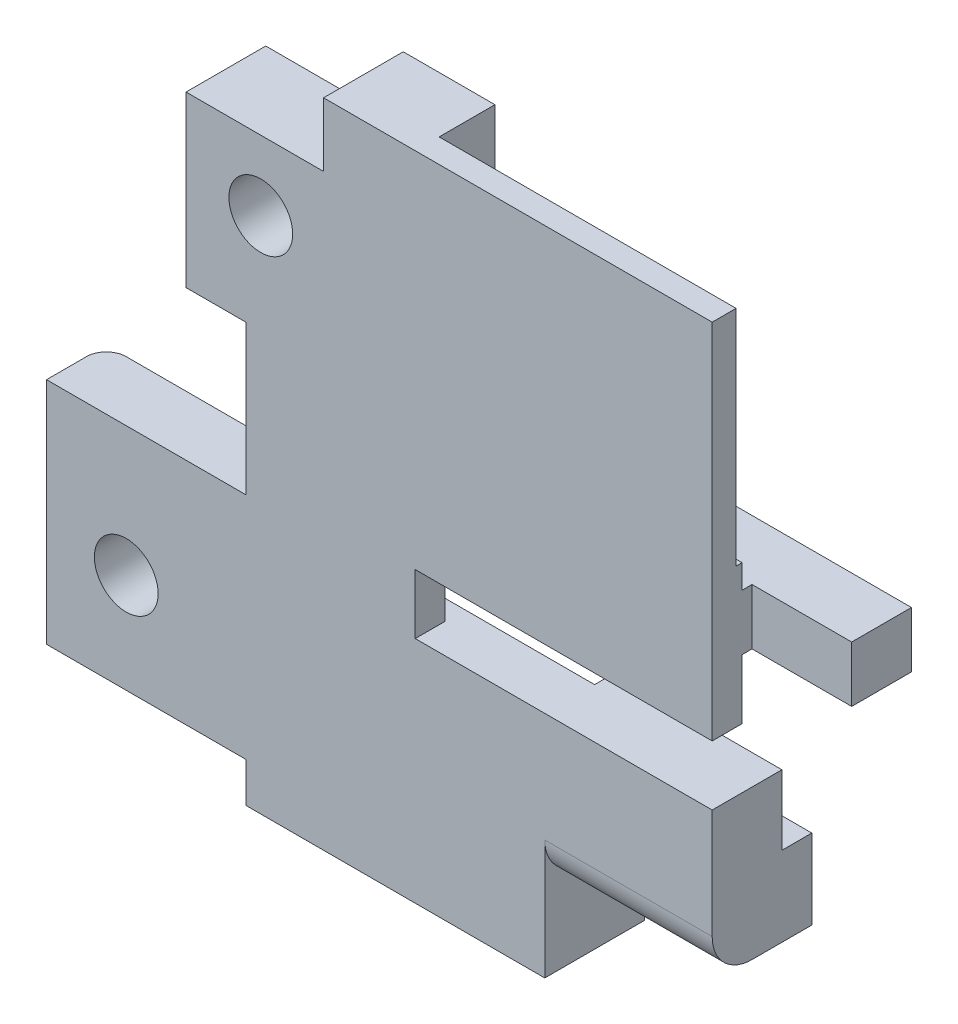
SolidWorks part; units mm, degrees
ref_plane "前视基准面" through (0, 0, 0) normal (0, 0, 1) x (1, 0, 0)
ref_plane "上视基准面" through (0, 0, 0) normal (0, 1, 0) x (1, 0, 0)
ref_plane "右视基准面" through (0, 0, 0) normal (1, 0, 0) x (0, 0, -1)
other "Configuration Table"
sketch "草图1" plane through (0, 0, 0) normal (0, 0, 1) x (1, 0, 0)
  line L1 (-4, 6.5) -> (6, 6.5)
  line L2 (-4, 6.5) -> (-4, -5)
  line L3 (-4, -5) -> (6, -5)
  line L4 (6, 6.5) -> (6, -5)
  circle A0 centre (0, 0) radius 1.6
  dimension "D1" = 3.2
  dimension "D2" = 5
  dimension "D3" = 4
  dimension "D4" = 11.5
  dimension "D5" = 10
extrude "凸台-拉伸1" add sketch "草图1" along normal blind 3
sketch "草图2" plane through (0, 0, 3) normal (0, 0, 1) x (1, 0, 0)
  line L1 (6, -5) -> (21, -5)
  line L2 (6, -5) -> (6, 1)
  line L3 (6, 1) -> (21, 1)
  line L4 (21, -5) -> (21, 1)
  dimension "D1" = 6
  dimension "D2" = 15
extrude "凸台-拉伸2" add sketch "草图2" against normal blind 5
fillet "圆角1" radius 1 1 edges at (-4, 0.75, 0)
sketch "草图3" plane through (0, 1, 0) normal (0, 1, 0) x (1, 0, 0)
  line L0 (21, -3) -> (6, -3) construction
  line L1 (6, 2) -> (11, 2)
  line L2 (6, 2) -> (6, -3)
  line L3 (6, -3) -> (11, -3)
  line L4 (11, 2) -> (11, -3)
  dimension "D1" = 5
extrude "凸台-拉伸3" add sketch "草图3" along normal blind 2
sketch "草图4" plane through (0, 3, 0) normal (0, 1, 0) x (1, 0, 0)
  line L0 (6, 2) -> (6, 0) construction
  line L1 (6, 0) -> (11, 0)
  line L2 (6, 0) -> (6, -3)
  line L3 (6, -3) -> (11, -3)
  line L4 (11, 0) -> (11, -3)
  dimension "D1" = 3
extrude "凸台-拉伸4" add sketch "草图4" along normal blind 19.5
sketch "草图5" plane through (0, 0, 0) normal (0, 0, -1) x (-1, 0, 0)
  line L0 (-6, 22.5) -> (-6, 6.5) construction
  line L1 (-6, 10) -> (-11, 10)
  line L2 (-6, 10) -> (-6, 13.5)
  line L3 (-6, 13.5) -> (-11, 13.5)
  line L4 (-11, 10) -> (-11, 13.5)
  line L5 (-11, 22.5) -> (-11, 3) construction
  line L6 (-11, 3) -> (-6, 3) construction
  line L7 (-11, 3) -> (-6, 3) construction
  dimension "D1" = 7
  dimension "D2" = 10.5
extrude "凸台-拉伸5" add sketch "草图5" along normal blind 3
sketch "草图6" plane through (6, 0, 0) normal (-1, 0, 0) x (0, 0, 1)
  line L1 (3, 22.5) -> (0, 22.5)
  line L2 (3, 22.5) -> (3, 14)
  line L3 (3, 14) -> (0, 14)
  line L4 (0, 22.5) -> (0, 14)
  line L5 (0, 22.5) -> (0, 13.5) construction
  dimension "D1" = 8.5
extrude "凸台-拉伸6" add sketch "草图6" along normal blind 3
sketch "草图7" plane through (0, 0, 0) normal (0, 0, -1) x (-1, 0, 0)
  line L6 (-11, 13.5) -> (-6, 13.5)
  line L7 (-6, 13.5) -> (-6, 14)
  line L8 (-6, 14) -> (-3, 14)
  line L9 (-3, 14) -> (-3, 22.5)
  line L10 (-3, 22.5) -> (-11, 22.5)
  line L11 (-11, 22.5) -> (-11, 13.5)
  line L12 (-11, 13.5) -> (-6, 13.5)
  line L13 (-6, 13.5) -> (-6, 14)
  line L14 (-6, 14) -> (-3, 14)
  line L15 (-3, 14) -> (-3, 22.5)
  line L16 (-3, 22.5) -> (-11, 22.5)
  line L17 (-11, 22.5) -> (-11, 13.5)
  dimension "D1" = 0
extrude "凸台-拉伸7" add sketch "草图7" along normal blind 1
sketch "草图8" plane through (0, 0, 3) normal (0, 0, 1) x (1, 0, 0)
  line L0 (21, 1) -> (11, 1) construction
  line L1 (11, 22.5) -> (14.5, 22.5)
  line L2 (11, 22.5) -> (11, 1)
  line L3 (11, 1) -> (14.5, 1)
  line L4 (14.5, 22.5) -> (14.5, 1)
  dimension "D1" = 3.5
extrude "凸台-拉伸8" add sketch "草图8" against normal blind 1
sketch "草图9" plane through (11, 0, 0) normal (1, 0, 0) x (0, 0, -1)
  line L0 (1, 22.5) -> (1, 13.5) construction
  line L1 (-2, 22.5) -> (1, 22.5)
  line L2 (-2, 22.5) -> (-2, 14.5)
  line L3 (-2, 14.5) -> (1, 14.5)
  line L4 (1, 22.5) -> (1, 14.5)
  dimension "D1" = 8
extrude "凸台-拉伸9" add sketch "草图9" along normal up to surface (3.5 mm away) up to face at (14.5, 11.75, 2.5)
sketch "草图10" plane through (11, 0, 0) normal (1, 0, 0) x (0, 0, -1)
  line L1 (-0.5, 4.5) -> (-3, 4.5)
  line L2 (-0.5, 4.5) -> (-0.5, 1)
  line L3 (-0.5, 1) -> (-3, 1)
  line L4 (-3, 4.5) -> (-3, 1)
  line L5 (-3, -5) -> (-3, 1) construction
  line L6 (2, 1) -> (-3, 1) construction
  line L7 (0, 10) -> (0, 3) construction
  dimension "D1" = 3.5
  dimension "D2" = 0.5
extrude "凸台-拉伸10" add sketch "草图10" along normal up to surface (10 mm away) up to face at (21, -2, 0.5)
sketch "草图11" plane through (11, 0, 0) normal (1, 0, 0) x (0, 0, -1)
  line L0 (-2, 14.5) -> (1, 14.5) construction
  line L1 (0, 14.5) -> (-3, 14.5)
  line L2 (0, 14.5) -> (0, 10.5)
  line L3 (0, 10.5) -> (-3, 10.5)
  line L4 (-3, 14.5) -> (-3, 10.5)
  line L5 (-3, 4.5) -> (-3, 22.5) construction
  dimension "D1" = 4
  dimension "D2" = 3
extrude "凸台-拉伸11" add sketch "草图11" along normal up to surface (10 mm away) up to face at (21, 0.1667, 0.5)
sketch "草图12" plane through (21, 0, 0) normal (1, 0, 0) x (0, 0, -1)
  line L1 (0, 14.5) -> (-1.5, 14.5)
  line L2 (0, 14.5) -> (0, 13.3)
  line L3 (0, 13.3) -> (-1.5, 13.3)
  line L4 (-1.5, 14.5) -> (-1.5, 13.3)
  dimension "D1" = 1.5
  dimension "D2" = 1.2
extrude "切除-拉伸1" cut sketch "草图12" against normal blind 2
sketch "草图13" plane through (14.5, 0, 0) normal (1, 0, 0) x (0, 0, -1)
  line L0 (-2, 10.5) -> (-2, 4.5) construction
  line L1 (-3, 10.5) -> (-2, 10.5)
  line L2 (-3, 10.5) -> (-3, 8)
  line L3 (-3, 8) -> (-2, 8)
  line L4 (-2, 10.5) -> (-2, 8)
  dimension "D1" = 2.5
extrude "凸台-拉伸12" add sketch "草图13" along normal up to surface (6.5 mm away) up to face at (21, 12.7667, 1.5)
sketch "草图14" plane through (14.5, 0, 0) normal (1, 0, 0) x (0, 0, -1)
  line L0 (1, 22.5) -> (-3, 22.5) construction
  line L1 (-1.8, 22.5) -> (-3, 22.5)
  line L2 (-1.8, 22.5) -> (-1.8, 14.5)
  line L3 (-1.8, 14.5) -> (-3, 14.5)
  line L4 (-3, 22.5) -> (-3, 14.5)
  dimension "D1" = 1.2
extrude "凸台-拉伸13" add sketch "草图14" along normal up to surface (6.5 mm away) up to face at (21, 11.575, 1.625)
sketch "草图15" plane through (0, 0, 1.8) normal (0, 0, -1) x (-1, 0, 0)
  line L1 (-14.5, 14.5) -> (-18.5, 14.5)
  line L2 (-14.5, 14.5) -> (-14.5, 18.5)
  line L3 (-14.5, 18.5) -> (-18.5, 18.5)
  line L4 (-18.5, 14.5) -> (-18.5, 18.5)
  dimension "D1" = 4
extrude "凸台-拉伸14" add sketch "草图15" along normal up to surface (2.8 mm away)
fillet "圆角2" radius 1 1 edges at (14.5, 18.5, 0.4)
sketch "草图16" plane through (0, 0, 3) normal (0, 0, 1) x (1, 0, 0)
  line L0 (3, 14) -> (3, 22.5) construction
  line L1 (3, 22.5) -> (21, 22.5) construction
  circle A0 centre (6.75, 19) radius 1.6
  dimension "D1" = 3.75
  dimension "D2" = 3.5
  dimension "D3" = 3.2
extrude "切除-拉伸2" cut sketch "草图16" against normal up to next
sketch "草图17" plane through (0, -5, 0) normal (0, -1, 0) x (1, 0, 0)
  line L1 (6, -2) -> (21, -2)
  line L2 (6, -2) -> (6, 3)
  line L3 (6, 3) -> (21, 3)
  line L4 (21, -2) -> (21, 3)
extrude "凸台-拉伸15" add sketch "草图17" along normal blind 2
sketch "草图18" plane through (21, 0, 0) normal (1, 0, 0) x (0, 0, -1)
  line L10 (0, 13.3) -> (-1.5, 13.3)
  line L11 (-1.5, 13.3) -> (-1.5, 14.5)
  line L12 (-1.5, 14.5) -> (-1.8, 14.5)
  line L13 (-1.8, 14.5) -> (-1.8, 22.5)
  line L14 (-1.8, 22.5) -> (-3, 22.5)
  line L15 (-3, 22.5) -> (-3, 8)
  line L16 (-3, 8) -> (-2, 8)
  line L17 (-2, 8) -> (-2, 10.5)
  line L18 (-2, 10.5) -> (0, 10.5)
  line L19 (0, 10.5) -> (0, 13.3)
  line L20 (0, 13.3) -> (-1.5, 13.3)
  line L21 (-1.5, 13.3) -> (-1.5, 14.5)
  line L22 (-1.5, 14.5) -> (-1.8, 14.5)
  line L23 (-1.8, 14.5) -> (-1.8, 22.5)
  line L24 (-1.8, 22.5) -> (-3, 22.5)
  line L25 (-3, 22.5) -> (-3, 8)
  line L26 (-3, 8) -> (-2, 8)
  line L27 (-2, 8) -> (-2, 10.5)
  line L28 (-2, 10.5) -> (0, 10.5)
  line L29 (0, 10.5) -> (0, 13.3)
  dimension "D1" = 0
extrude "凸台-拉伸16" add sketch "草图18" along normal blind 5.5
sketch "草图19" plane through (0, 0, 0) normal (0, 0, -1) x (-1, 0, 0)
  line L0 (-19, 13.3) -> (-26.5, 13.3) construction
  line L1 (-24.5, 13.3) -> (-26.5, 13.3)
  line L2 (-24.5, 13.3) -> (-24.5, 10.5)
  line L3 (-24.5, 10.5) -> (-26.5, 10.5)
  line L4 (-26.5, 13.3) -> (-26.5, 10.5)
  dimension "D1" = 2
extrude "凸台-拉伸17" add sketch "草图19" along normal blind 2
sketch "草图20" plane through (21, 0, 0) normal (1, 0, 0) x (0, 0, -1)
  line L1 (0.5, -3) -> (-3, -3)
  line L2 (0.5, 1) -> (0.5, 4.5)
  line L3 (0.5, 4.5) -> (-3, 4.5)
  line L4 (-3, -3) -> (-3, 4.5)
  line L5 (2, -7) -> (2, 1) construction
  line L7 (2, 1) -> (0.5, 1)
  line L8 (2, 1) -> (2, -3)
  line L9 (2, -3) -> (0.5, -3)
  dimension "D1" = 1.5
  dimension "D2" = 7.5
extrude "凸台-拉伸18" add sketch "草图20" along normal up to surface (5.5 mm away) up to face at (26.5, 13.76, 1.26)
sketch "草图21" plane through (26.5, 0, 0) normal (1, 0, 0) x (0, 0, -1)
  line L6 (-3, -3) -> (2, -3)
  line L7 (2, -3) -> (2, 1)
  line L8 (2, 1) -> (0.5, 1)
  line L9 (0.5, 1) -> (0.5, 4.5)
  line L10 (0.5, 4.5) -> (-3, 4.5)
  line L11 (-3, 4.5) -> (-3, -3)
  line L12 (-3, -3) -> (2, -3)
  line L13 (2, -3) -> (2, 1)
  line L14 (2, 1) -> (0.5, 1)
  line L15 (0.5, 1) -> (0.5, 4.5)
  line L16 (0.5, 4.5) -> (-3, 4.5)
  line L17 (-3, 4.5) -> (-3, -3)
  line L22 (-2, 10.5) -> (2, 10.5)
  line L23 (2, 10.5) -> (2, 13.3)
  line L24 (2, 13.3) -> (-1.5, 13.3)
  line L25 (-1.5, 13.3) -> (-1.5, 14.5)
  line L26 (-1.5, 14.5) -> (-1.8, 14.5)
  line L27 (-1.8, 14.5) -> (-1.8, 22.5)
  line L28 (-1.8, 22.5) -> (-3, 22.5)
  line L29 (-3, 22.5) -> (-3, 8)
  line L30 (-3, 8) -> (-2, 8)
  line L31 (-2, 8) -> (-2, 10.5)
  line L32 (-2, 10.5) -> (2, 10.5)
  line L33 (2, 10.5) -> (2, 13.3)
  line L34 (2, 13.3) -> (-1.5, 13.3)
  line L35 (-1.5, 13.3) -> (-1.5, 14.5)
  line L36 (-1.5, 14.5) -> (-1.8, 14.5)
  line L37 (-1.8, 14.5) -> (-1.8, 22.5)
  line L38 (-1.8, 22.5) -> (-3, 22.5)
  line L39 (-3, 22.5) -> (-3, 8)
  line L40 (-3, 8) -> (-2, 8)
  line L41 (-2, 8) -> (-2, 10.5)
  dimension "D1" = 0
  dimension "D2" = 0
extrude "凸台-拉伸19" add sketch "草图21" along normal blind 2.9
sketch "草图22" plane through (0, 0, 2) normal (0, 0, -1) x (-1, 0, 0)
  line L6 (-11, 10.5) -> (-29.4, 10.5)
  line L7 (-29.4, 10.5) -> (-29.4, 8)
  line L8 (-29.4, 8) -> (-14.5, 8)
  line L9 (-14.5, 8) -> (-14.5, 4.5)
  line L10 (-14.5, 4.5) -> (-11, 4.5)
  line L11 (-11, 4.5) -> (-11, 10.5)
  line L12 (-11, 10.5) -> (-29.4, 10.5)
  line L13 (-29.4, 10.5) -> (-29.4, 8)
  line L14 (-29.4, 8) -> (-14.5, 8)
  line L15 (-14.5, 8) -> (-14.5, 4.5)
  line L16 (-14.5, 4.5) -> (-11, 4.5)
  line L17 (-11, 4.5) -> (-11, 10.5)
  dimension "D1" = 0
extrude "凸台-拉伸20" add sketch "草图22" along normal blind 0.5
fillet "圆角3" radius 2 1 edges at (25.2, -3, 3)
sketch "草图23" plane through (0, 8, 0) normal (0, -1, 0) x (1, 0, 0)
  line L4 (14.5, 3) -> (14.5, 1.5)
  line L5 (14.5, 1.5) -> (29.4, 1.5)
  line L6 (29.4, 1.5) -> (29.4, 3)
  line L7 (29.4, 3) -> (14.5, 3)
  line L8 (14.5, 3) -> (14.5, 1.5)
  line L9 (14.5, 1.5) -> (29.4, 1.5)
  line L10 (29.4, 1.5) -> (29.4, 3)
  line L11 (29.4, 3) -> (14.5, 3)
  dimension "D1" = 0
extrude "凸台-拉伸21" add sketch "草图23" along normal blind 0.5
sketch "草图24" plane through (29.4, 0, 0) normal (1, 0, 0) x (0, 0, -1)
  line L0 (-1.5, 10.5) -> (0, 10.5) construction
  line L1 (2, 13.3) -> (-1, 13.3)
  line L2 (2, 13.3) -> (2, 10.5)
  line L3 (2, 10.5) -> (-1, 10.5)
  line L4 (-1, 13.3) -> (-1, 10.5)
  dimension "D1" = 3
extrude "凸台-拉伸22" add sketch "草图24" along normal blind 5
sketch "草图25" plane through (0, 22.5, 0) normal (0, 1, 0) x (1, 0, 0)
  line L0 (9.9, 1) -> (9.9, -3)
  line L6 (14.5, -1.8) -> (14.5, 1)
  line L7 (14.5, 1) -> (3, 1)
  line L8 (3, 1) -> (3, -3)
  line L9 (3, -3) -> (29.4, -3)
  line L10 (29.4, -3) -> (29.4, -1.8)
  line L11 (29.4, -1.8) -> (14.5, -1.8)
  line L12 (14.5, -1.8) -> (14.5, 1)
  line L13 (14.5, 1) -> (9.9, 1)
  line L15 (9.9, -3) -> (29.4, -3)
  line L16 (29.4, -3) -> (29.4, -1.8)
  line L17 (29.4, -1.8) -> (14.5, -1.8)
  dimension "D2" = 19.5
  dimension "D1" = 0
extrude "凸台-拉伸23" add sketch "草图25" along normal blind 3.2
equation "\"。5\"=10"
